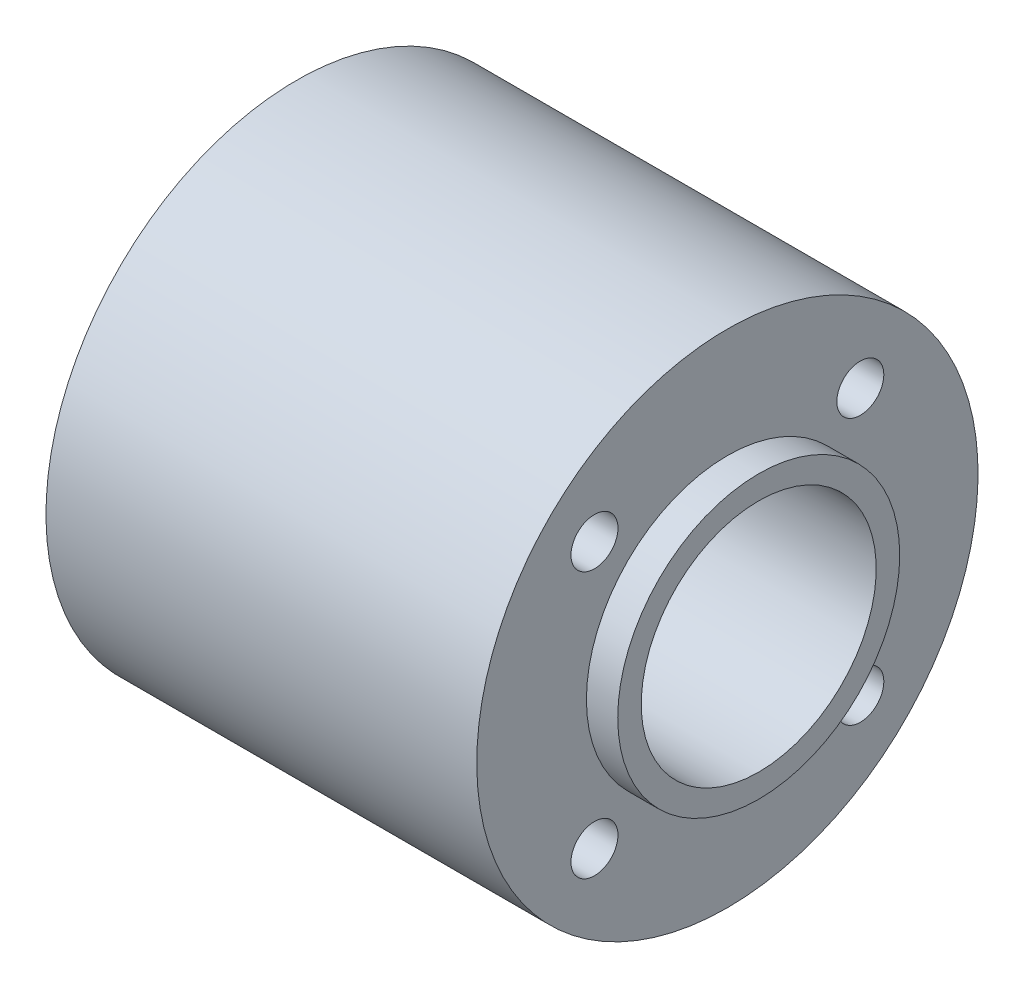
SolidWorks part; units mm, degrees
ref_plane "Front Plane" through (0, 0, 0) normal (0, 0, 1) x (1, 0, 0)
ref_plane "Top Plane" through (0, 0, 0) normal (0, 1, 0) x (1, 0, 0)
ref_plane "Right Plane" through (0, 0, 0) normal (1, 0, 0) x (0, 0, -1)
sketch "Sketch1" plane through (0, 0, 0) normal (0, 0, 1) x (1, 0, 0)
  line L0 (0, 0) -> (28.6909, 0) construction
  line L1 (0, 0) -> (0, 16) construction
  line L2 (15.75, 0) -> (15.75, 9)
  line L3 (15.75, 9) -> (13.75, 9)
  line L4 (13.75, 9) -> (13.75, 16)
  line L5 (13.75, 16) -> (-13.75, 16)
  line L6 (-15.75, 9) -> (-13.75, 9)
  line L7 (-15.75, 0) -> (-15.75, 9)
  line L8 (-13.75, 9) -> (-13.75, 16)
  line L9 (-15.75, 0) -> (15.75, 0)
  dimension "D1" = 9
  dimension "D2" = 2
  dimension "D3" = 13.75
  dimension "D4" = 16
revolve "Revolve1" add sketch "Sketch1" angle 360 about L9
sketch "Sketch2" plane through (15.75, 0, 0) normal (1, 0, 0) x (0, 0, -1)
  circle A0 centre (0, 0) radius 7.5
extrude "Cut-Extrude1" cut sketch "Sketch2" against normal through all both and the other way through all
sketch "Sketch3" plane through (13.75, 0, 0) normal (1, 0, 0) x (0, 0, -1)
  line L0 (0, 12) -> (0, 0) construction
  line L1 (0, 0) -> (-8.4853, 8.4853) construction
  circle A0 centre (0, 0) radius 12 construction
  circle A1 centre (-8.4853, 8.4853) radius 1.5
  circle A2 centre (8.4853, 8.4853) radius 1.5
  circle A3 centre (8.4853, -8.4853) radius 1.5
  circle A4 centre (-8.4853, -8.4853) radius 1.5
  circle A5 centre (0, 0) radius 16 construction
  point P15 (0, 0)
  dimension "D1" = 24
  dimension "D3" = 4
  dimension "D4" = 3
  dimension "D5" = 8.4853
  dimension "D2" = 45
extrude "Cut-Extrude2" cut sketch "Sketch3" against normal through all both and the other way through all
